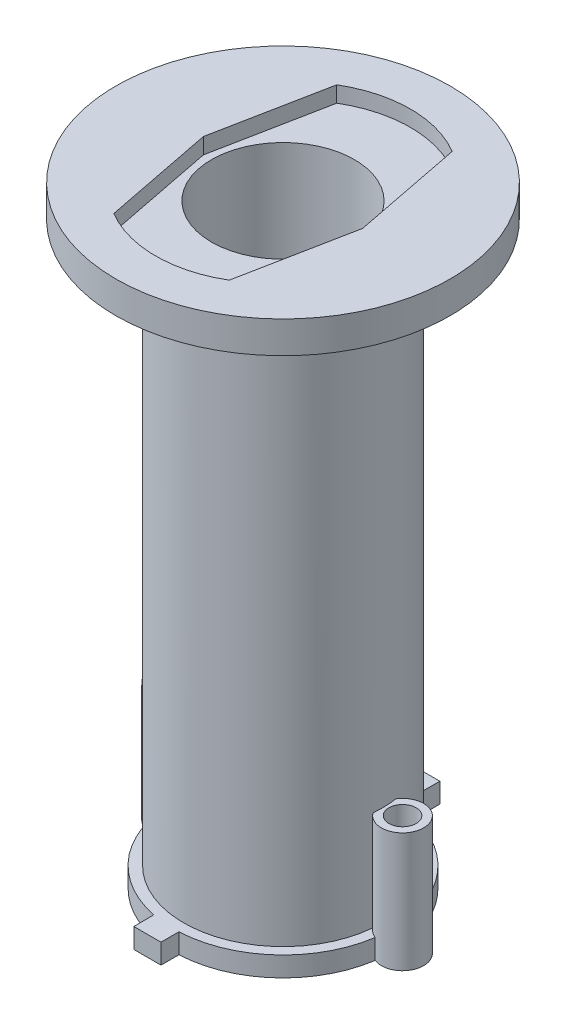
SolidWorks part; units mm, degrees
material "ABS"
ref_plane "Front Plane" through (0, 0, 0) normal (0, 0, 1) x (1, 0, 0)
ref_plane "Top Plane" through (0, 0, 0) normal (0, 1, 0) x (1, 0, 0)
ref_plane "Right Plane" through (0, 0, 0) normal (1, 0, 0) x (0, 0, -1)
sketch "Sketch1" plane through (0, 0, 0) normal (0, 1, 0) x (1, 0, 0)
  line L0 (14.5034, -1.0795) -> (-14.5034, -1.0795) construction
  line L1 (0.598, 12.2364) -> (0.598, 17.5133)
  line L2 (0.598, 17.5133) -> (-2.8194, 17.5133)
  line L3 (-2.8194, 17.5133) -> (-2.8194, 11.9769)
  line L4 (-2.8194, -15.0046) -> (-2.8194, -17.5133)
  line L5 (-2.8194, -17.5133) -> (0.598, -17.5133)
  line L6 (0.598, -17.5133) -> (0.598, -15.2641)
  arc A0 (-2.8194, 11.9769) -> (-13.533, 1.3911) centre (-0.0762, -1.5138) ccw
  arc A1 (-13.533, 1.3911) -> (-13.6834, -3.604) centre (-14.5034, -1.0795) ccw
  arc A2 (-13.6834, -3.604) -> (-2.8194, -15.0046) centre (-0.0762, -1.5138) ccw
  arc A3 (0.598, -15.2641) -> (13.5388, -3.5523) centre (-0.0762, -1.5138) ccw
  arc A4 (13.5388, -3.5523) -> (13.3933, 1.3315) centre (14.5034, -1.0795) ccw
  arc A5 (13.3933, 1.3315) -> (0.598, 12.2364) centre (-0.0762, -1.5138) ccw
  dimension "D1" = 13.7668
  dimension "D2" = 2.6543
  dimension "D6" = 13.7668
  dimension "D15" = 2.6543
  dimension "D3" = 2.5087
  dimension "D4" = 2.2492
  dimension "D5" = 3.4174
  dimension "D7" = 14.5796
  dimension "D8" = 14.4272
  dimension "D9" = 5.2769
  dimension "D10" = 5.5364
  dimension "D11" = 3.4174
  dimension "D12" = 0.6742
  dimension "D13" = 2.7432
  dimension "D14" = 0.4343
extrude "Boss-Extrude1" add sketch "Sketch1" along normal blind 2.5
sketch "Sketch2" plane through (0, 2.5, 0) normal (0, 1, 0) x (1, 0, 0)
  circle A1 centre (-14.5034, -1.0795) radius 1.715
  circle A2 centre (14.5034, -1.0795) radius 1.715
  circle A3 centre (-0.0762, -1.5138) radius 8.98
  dimension "D1" = 3.43
  dimension "D2" = 3.43
  dimension "D3" = 17.96
extrude "Cut-Extrude1" cut sketch "Sketch2" against normal up to next contours A1 | A2 | A3
sketch "Sketch3" plane through (0, 2.5, 0) normal (0, 1, 0) x (1, 0, 0)
  circle A0 centre (-14.5034, -1.0795) radius 2.6543
  circle A1 centre (14.5034, -1.0795) radius 2.6543
extrude "Boss-Extrude2" add sketch "Sketch3" along normal blind 70.305
sketch "Sketch4" plane through (0, 72.805, 0) normal (0, 1, 0) x (1, 0, 0)
  circle A0 centre (-0.0762, -1.5138) radius 8.98
  circle A1 centre (-0.0762, -1.5138) radius 21
  dimension "D1" = 42
extrude "Boss-Extrude3" add sketch "Sketch4" along normal blind 4
sketch "Sketch5" plane through (0, 76.805, 0) normal (0, 1, 0) x (1, 0, 0)
  line L0 (-0.0762, -1.5104) -> (-7.4262, -1.5104) construction
  line L1 (-7.4262, 12.1396) -> (-10.0762, -1.5104)
  line L2 (-10.0762, -1.5104) -> (-7.4262, -15.1604)
  line L3 (7.2738, -15.1604) -> (9.9238, -1.5104)
  line L4 (9.9238, -1.5104) -> (7.2738, 12.1396)
  circle A0 centre (-0.0762, -1.5104) radius 21
  arc A1 (-7.4262, 12.1396) -> (7.2738, 12.1396) centre (-0.0762, -1.5069) cw
  arc A2 (-7.4262, -15.1604) -> (7.2738, -15.1604) centre (-0.0762, -1.5138) ccw
  point P11 (-0.0762, -1.5138)
  dimension "D5" = 15.5
  dimension "D6" = 15.5
  dimension "D1" = 14.7
  dimension "D2" = 27.3
  dimension "D3" = 10
  dimension "D4" = 10
ref_plane "Plane1" through (0, 37.805, 0) normal (0, -1, 0) x (-1, 0, 0)
sketch "Sketch6" plane through (0, 37.805, 0) normal (0, -1, 0) x (-1, 0, 0)
  circle A0 centre (0.0762, -1.5138) radius 21
  circle A1 centre (0.0762, -1.5138) radius 8.98
extrude "Boss-Extrude4" add sketch "Sketch6" along normal blind 2
sketch "Sketch7" plane through (0, 0, 0) normal (0, -1, 0) x (1, 0, 0)
  circle A0 centre (-14.5034, 1.0795) radius 1.715
  circle A1 centre (14.5034, 1.0795) radius 1.715
extrude "Cut-Extrude3" cut sketch "Sketch7" against normal blind 15
sketch "Sketch8" plane through (0, 76.805, 0) normal (0, 1, 0) x (1, 0, 0)
  line L0 (-10.0762, -1.5138) -> (9.9238, -1.5138) construction
  line L1 (9.9238, -17.5138) -> (-10.0762, -17.5138) construction
  line L2 (9.9238, -17.5138) -> (9.9238, 14.4862) construction
  line L3 (9.9238, 14.4862) -> (-10.0762, 14.4862) construction
  line L4 (-10.0762, -17.5138) -> (-10.0762, 14.4862) construction
  line L5 (9.9238, -17.5138) -> (-10.0762, 14.4862) construction
  line L6 (9.9238, 14.4862) -> (-10.0762, -17.5138) construction
  line L7 (7.1738, -15.5138) -> (-7.3262, -15.5138) construction
  line L8 (7.1738, -15.5138) -> (7.1738, 12.4862) construction
  line L9 (7.1738, 12.4862) -> (-7.3262, 12.4862) construction
  line L10 (-7.3262, -15.5138) -> (-7.3262, 12.4862) construction
  line L11 (7.1738, -15.5138) -> (-7.3262, 12.4862) construction
  line L12 (7.1738, 12.4862) -> (-7.3262, -15.5138) construction
  line L13 (-10.0762, -1.5138) -> (-7.3262, -15.5138)
  line L14 (7.1738, -15.5138) -> (9.9238, -1.5138)
  line L15 (9.9238, -1.5138) -> (7.1738, 12.4862)
  line L16 (-7.3262, 12.4862) -> (-10.0762, -1.5138)
  circle A0 centre (-0.0762, -1.5138) radius 8.98
  arc A1 (-7.3262, 12.4862) -> (7.1738, 12.4862) centre (-0.0762, 0.3455) cw
  arc A2 (-7.3262, -15.5138) -> (7.1738, -15.5138) centre (-0.0762, -3.3732) ccw
  dimension "D1" = 32
  dimension "D2" = 20
  dimension "D3" = 14.5
  dimension "D4" = 28
extrude "Cut-Extrude4" cut sketch "Sketch8" against normal blind 2
sketch "Sketch9" plane through (0, 0, 0) normal (0, -1, 0) x (1, 0, 0)
  circle A0 centre (-0.0762, 1.5138) radius 8.9789
  circle A1 centre (-0.0762, 1.5138) radius 11.0744
  circle A2 centre (-0.0762, 1.5138) radius 8.98
sketch "Sketch10" plane through (0, 2.5, 0) normal (0, 1, 0) x (1, 0, 0)
  circle A0 centre (-0.0762, -1.5138) radius 8.98
  circle A1 centre (-0.0762, -1.5138) radius 12.48
  dimension "D1" = 3.5
extrude "Boss-Extrude6" add sketch "Sketch10" along normal up to surface (70.305 mm away) up to face at (-14.5034, 72.805, 3.7338)
sketch "Sketch12" plane through (0, 15, 0) normal (0, -1, 0) x (1, 0, 0)
  circle A0 centre (-0.0762, 1.5138) radius 21
  circle A1 centre (-0.0762, 1.5138) radius 8.98 construction
  circle A2 centre (-0.0762, 1.5138) radius 12.48
  dimension "D1" = 3.5
extrude "Cut-Extrude5" cut sketch "Sketch12" against normal up to surface (57.805 mm away) up to face at (-0.0762, 72.805, 22.5138)
